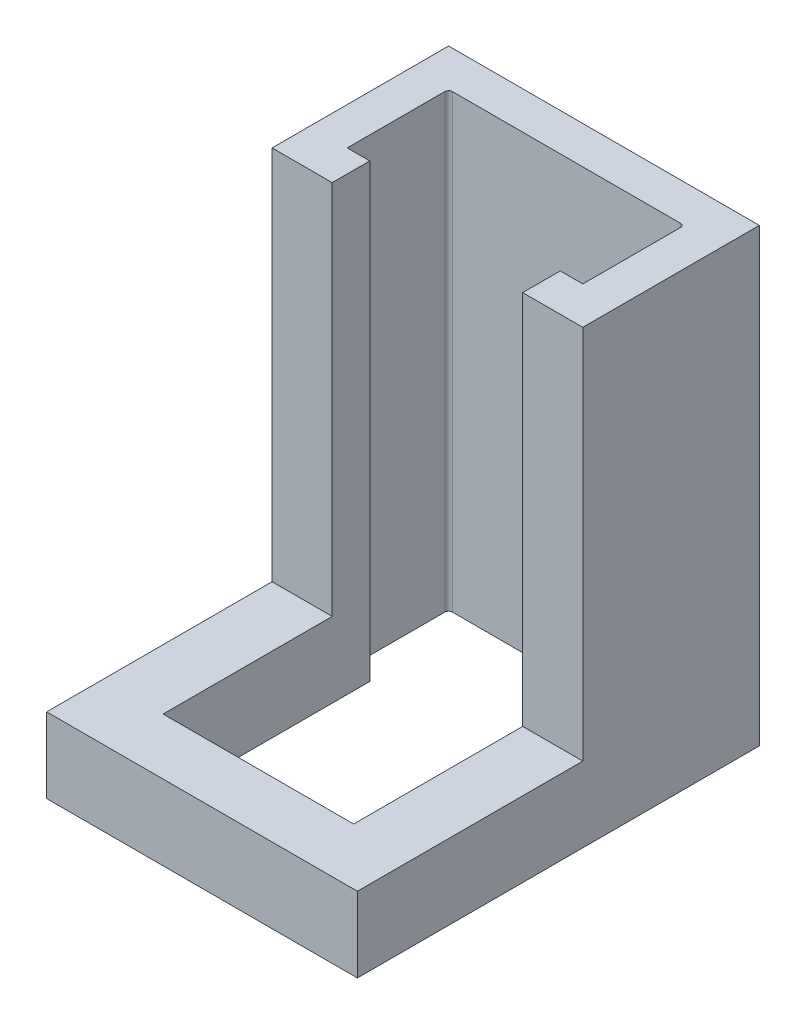
SolidWorks part; units mm, degrees
ref_plane "Front Plane" through (0, 0, 0) normal (0, 0, 1) x (1, 0, 0)
ref_plane "Top Plane" through (0, 0, 0) normal (0, 1, 0) x (1, 0, 0)
ref_plane "Right Plane" through (0, 0, 0) normal (1, 0, 0) x (0, 0, -1)
sketch "Sketch1" plane through (0, 0, 0) normal (0, 1, 0) x (1, 0, 0)
  line L0 (15.6766, 0) -> (15.6766, 12.9937)
  line L1 (15.1766, 13.4937) -> (-15.1766, 13.4937)
  line L2 (0, 13.4937) -> (0, 18.4937) construction
  line L3 (-20.6766, 18.4937) -> (20.6766, 18.4937)
  line L4 (20.6766, 18.4937) -> (20.6766, 0)
  line L7 (-20.6766, 18.4937) -> (-20.6766, 0)
  line L8 (-15.6766, 0) -> (-15.6766, 12.9937)
  line L9 (-15.6766, 0) -> (-12.6766, 0)
  line L10 (-12.6766, 0) -> (-12.6766, -5)
  line L11 (-12.6766, -5) -> (-20.6766, -5)
  line L12 (-20.6766, -5) -> (-20.6766, 0)
  line L13 (15.6766, 0) -> (12.6766, 0)
  line L14 (20.6766, -5) -> (20.6766, 0)
  line L15 (12.6766, -5) -> (20.6766, -5)
  line L16 (12.6766, 0) -> (12.6766, -5)
  line L17 (-15.6766, 0) -> (-20.6766, 0) construction
  arc A0 (15.6766, 12.9937) -> (15.1766, 13.4937) centre (15.1766, 12.9937) ccw
  arc A1 (-15.6766, 12.9937) -> (-15.1766, 13.4937) centre (-15.1766, 12.9937) cw
  point P15 (15.6766, 13.4937)
  point P18 (-15.6766, 13.4937)
  dimension "D4" = 0.5
  dimension "D1" = 31.3531
  dimension "D2" = 13.4937
  dimension "D3" = 5
  dimension "D5" = 3
extrude "Boss-Extrude1" add sketch "Sketch1" along normal blind 50
sketch "Sketch2" plane through (0, 0, 0) normal (0, -1, 0) x (1, 0, 0)
  line L0 (-20.6766, -18.4937) -> (-20.6766, 5) construction
  line L1 (-12.6766, 5) -> (-12.6766, 0) construction
  line L2 (-12.6766, 0) -> (-15.6766, 0) construction
  line L3 (-15.6766, 0) -> (-15.6766, -12.9937) construction
  line L4 (20.6766, -18.4937) -> (-20.6766, -18.4937) construction
  line L5 (-15.1766, -13.4937) -> (15.1766, -13.4937) construction
  line L6 (15.6766, -12.9937) -> (15.6766, 0) construction
  line L7 (15.6766, 0) -> (12.6766, 0) construction
  line L8 (12.6766, 0) -> (12.6766, 5) construction
  line L9 (20.6766, 5) -> (20.6766, -18.4937) construction
  line L10 (-20.6766, -18.4937) -> (-20.6766, 5)
  line L11 (-12.6766, 5) -> (-12.6766, 0)
  line L12 (-12.6766, 0) -> (-15.6766, 0)
  line L13 (-15.6766, 0) -> (-15.6766, -12.9937)
  line L14 (20.6766, -18.4937) -> (-20.6766, -18.4937)
  line L15 (-15.1766, -13.4937) -> (15.1766, -13.4937)
  line L16 (15.6766, -12.9937) -> (15.6766, 0)
  line L17 (15.6766, 0) -> (12.6766, 0)
  line L18 (12.6766, 0) -> (12.6766, 5)
  line L19 (20.6766, 5) -> (20.6766, -18.4937)
  line L20 (20.6766, 5) -> (20.6766, 35)
  line L21 (20.6766, 35) -> (-20.6766, 35)
  line L22 (-20.6766, 35) -> (-20.6766, 5)
  line L23 (-12.6766, 5) -> (-12.6766, 27.5)
  line L24 (-12.6766, 27.5) -> (12.6766, 27.5)
  line L25 (12.6766, 27.5) -> (12.6766, 5)
  arc A0 (-15.6766, -12.9937) -> (-15.1766, -13.4937) centre (-15.1766, -12.9937) ccw construction
  arc A1 (15.1766, -13.4937) -> (15.6766, -12.9937) centre (15.1766, -12.9937) ccw construction
  arc A2 (-15.6766, -12.9937) -> (-15.1766, -13.4937) centre (-15.1766, -12.9937) ccw
  arc A3 (15.1766, -13.4937) -> (15.6766, -12.9937) centre (15.1766, -12.9937) ccw
  dimension "D1" = 7.5
  dimension "D2" = 30
extrude "Boss-Extrude2" add sketch "Sketch2" along normal blind 10
sketch "Sketch3" plane through (0, 0, -18.4937) normal (0, 0, -1) x (-1, 0, 0)
  circle A0 centre (0, 10) radius 1.5
  circle A1 centre (0, 20) radius 1.5
  circle A2 centre (0, 30) radius 1.5
  dimension "D1" = 3
  dimension "D3" = 10
  dimension "D4" = 10
  dimension "D2" = 3
extrude "Cut-Extrude1" cut sketch "Sketch3" against normal up to next
